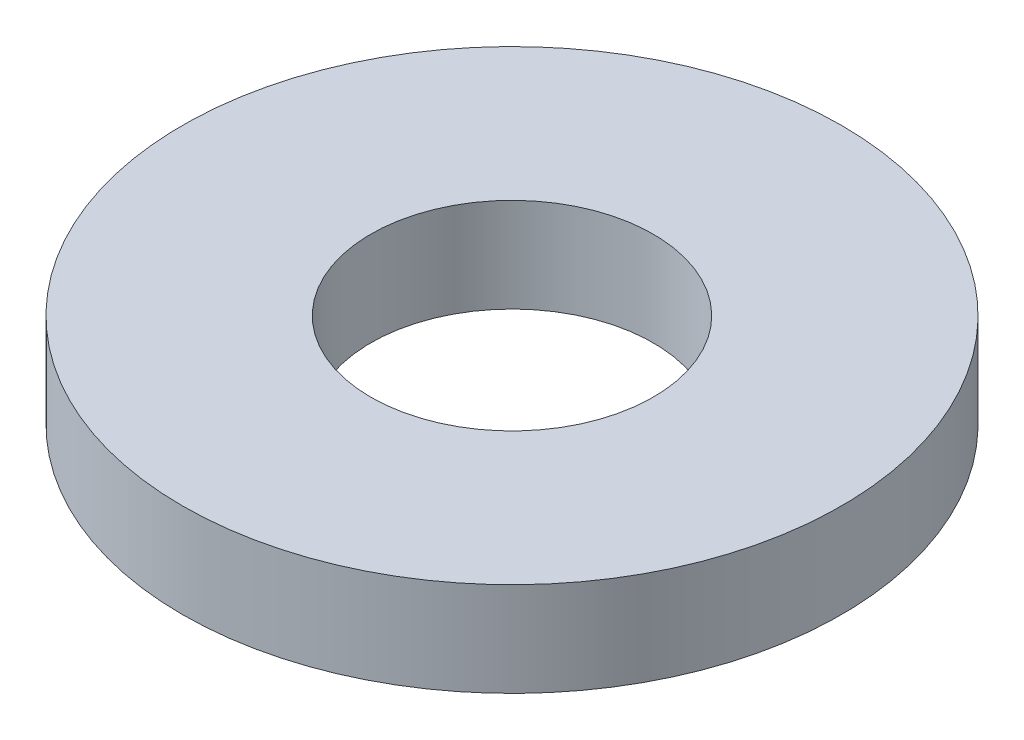
SolidWorks part; units mm, degrees
ref_plane "前视基准面" through (0, 0, 0) normal (0, 0, 1) x (1, 0, 0)
ref_plane "上视基准面" through (0, 0, 0) normal (0, 1, 0) x (1, 0, 0)
ref_plane "右视基准面" through (0, 0, 0) normal (1, 0, 0) x (0, 0, -1)
sketch "草图1" plane through (0, 0, 0) normal (0, 1, 0) x (1, 0, 0)
  circle A0 centre (0, 0) radius 3
  circle A1 centre (0, 0) radius 7
  dimension "D1" = 6
  dimension "D2" = 14
extrude "凸台-拉伸1" add sketch "草图1" along normal blind 2
